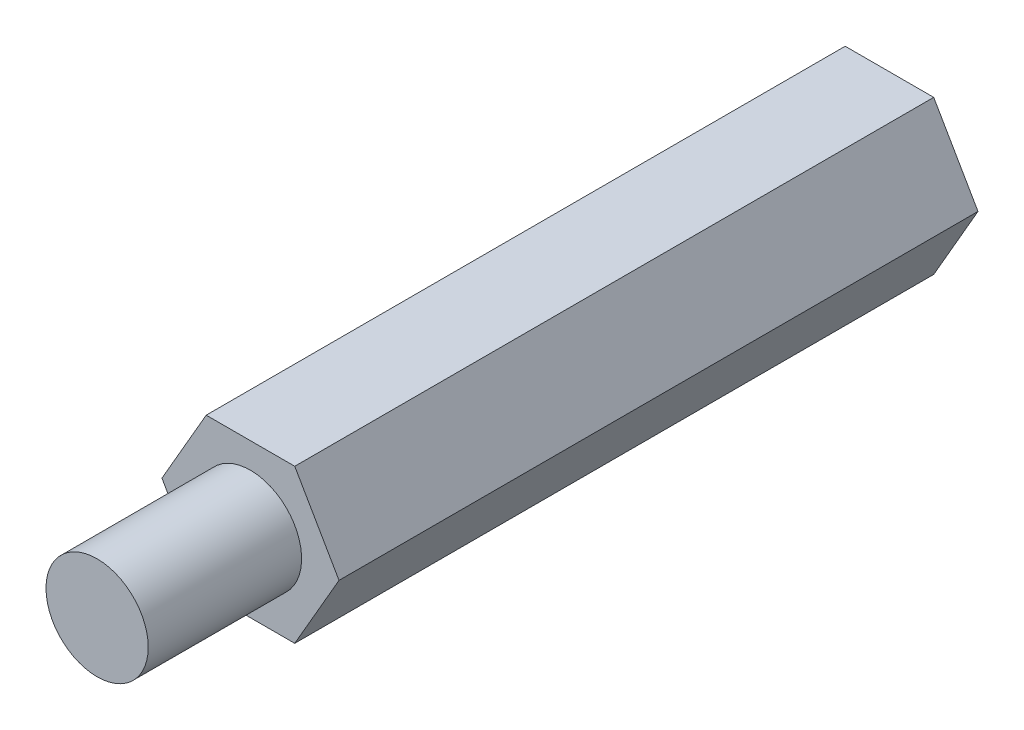
SolidWorks part; units mm, degrees
ref_plane "前视基准面" through (0, 0, 0) normal (0, 0, 1) x (1, 0, 0)
ref_plane "上视基准面" through (0, 0, 0) normal (0, 1, 0) x (1, 0, 0)
ref_plane "右视基准面" through (0, 0, 0) normal (1, 0, 0) x (0, 0, -1)
sketch "草图1" plane through (0, 0, 0) normal (0, 0, 1) x (1, 0, 0)
  line L0 (-28.6627, 0) -> (33.6774, 0) construction
  line L1 (1.7321, -3) -> (3.4641, 0)
  line L2 (3.4641, 0) -> (1.7321, 3)
  line L3 (1.7321, 3) -> (-1.7321, 3)
  line L4 (-1.7321, 3) -> (-3.4641, 0)
  line L5 (-3.4641, 0) -> (-1.7321, -3)
  line L6 (-1.7321, -3) -> (1.7321, -3)
  circle A0 centre (0, 0) radius 3 construction
  dimension "D1" = 6
extrude "拉伸1" add sketch "草图1" along normal blind 25
sketch "草图2" plane through (0, 0, 25) normal (0, 0, 1) x (1, 0, 0)
  circle A0 centre (0, 0) radius 2
  dimension "D1" = 4
extrude "拉伸2" add sketch "草图2" along normal blind 6
hole_wizard "M4 螺纹孔1" positions "3D草图2" profile "草图5" tap size "M4" standard "ISO"
sketch3d "3D草图2"
  point P0 (0, 0, 0)
  point P2 (0, 0, 0)
  point P3 (0, 0, 0)
  point P4 (0, 0, 0)
cosmetic thread "孔螺蚊线1" parameters "D1"=8, "D2"=4
sketch "草图5" plane through (0, 0, 0) normal (1, 0, 0) x (0, 1, 0)
  line L0 (0, 0) -> (0, 12.4914)
  line L1 (0, 12.4914) -> (1.65, 11.5)
  line L2 (1.65, 11.5) -> (1.65, 0)
  line L5 (1.65, 0) -> (0, 0)
  line L10 (0, 12.4914) -> (-1.65, 11.5) construction
  line L11 (0, -6.35) -> (0, 107.95) construction
  dimension "蹟恇謂郰芛眻噤" = 3.3
  dimension "蹟恇謂郰芛旮僅" = 11.5
  dimension "絳芛褒僅" = 118
cosmetic thread "孔螺蚊线2" parameters "D1"=8, "D2"=4
cosmetic thread "孔螺蚊线3" parameters "D1"=8, "D2"=4
cosmetic thread "孔螺蚊线4" parameters "D1"=8, "D2"=4
sketch "草图6" plane through (0, 0, 0) normal (0, 0, -1) x (-1, 0, 0)
  circle A0 centre (0, 0) radius 1.5
  dimension "D1" = 3
extrude "拉伸3" [suppressed] add sketch "草图6" along normal blind 10
